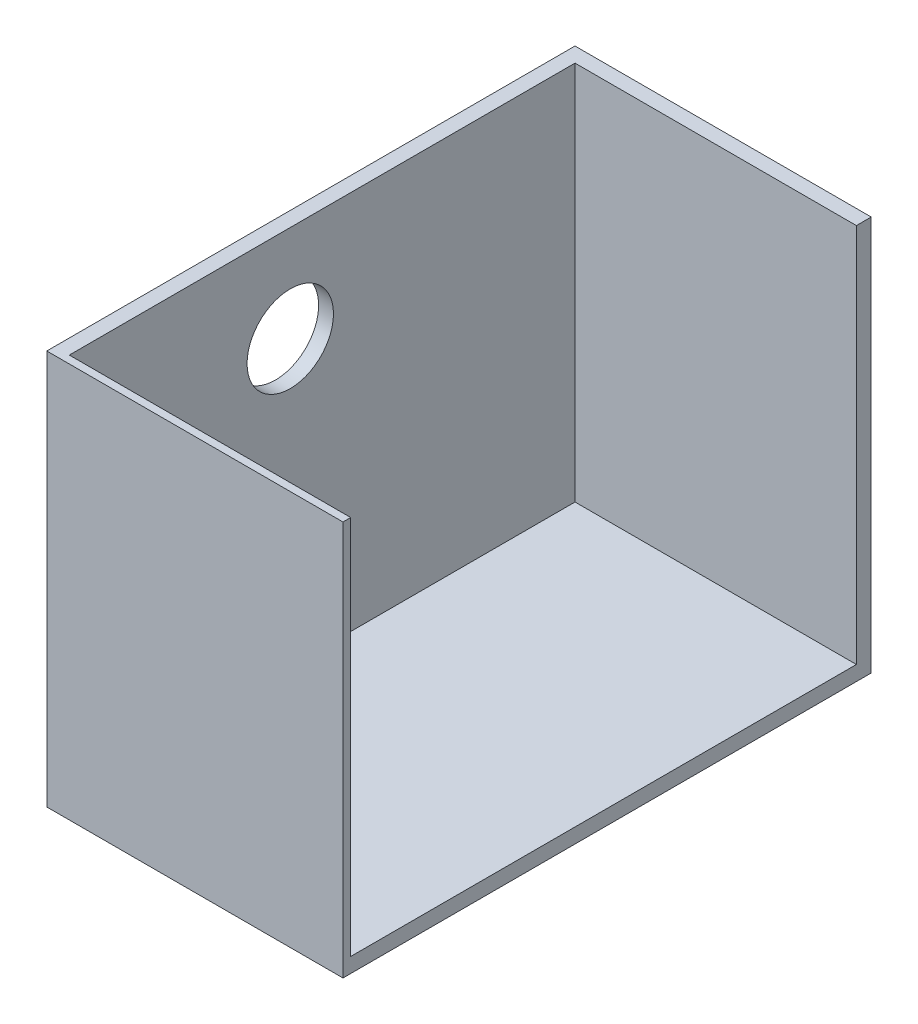
SolidWorks part; units mm, degrees
ref_plane "Front Plane" through (0, 0, 0) normal (0, 0, 1) x (1, 0, 0)
ref_plane "Top Plane" through (0, 0, 0) normal (0, 1, 0) x (1, 0, 0)
ref_plane "Right Plane" through (0, 0, 0) normal (1, 0, 0) x (0, 0, -1)
sketch "Sketch1" plane through (0, 0, 0) normal (0, 1, 0) x (1, 0, 0)
  line L1 (-60, -107) -> (60, -107)
  line L2 (-60, -107) -> (-60, 107)
  line L3 (-60, 107) -> (60, 107)
  line L4 (60, -107) -> (60, 107)
  line L5 (-60, -107) -> (60, 107) construction
  line L6 (-60, 107) -> (60, -107) construction
  point P0 (0, 0)
  dimension "D1" = 120
  dimension "D2" = 214
extrude "Boss-Extrude1" add sketch "Sketch1" along normal blind 160
fillet "Fillet1" [suppressed] radius 80
fillet "Fillet4" [suppressed] radius 30
fillet "Fillet3" [suppressed] radius 80
shell "Shell1" thickness 6
ref_plane "Plane1" through (0, 101, 0) normal (0, -1, 0) x (-1, 0, 0)
sketch "Sketch4" plane through (-60, 0, 0) normal (-1, 0, 0) x (0, 0, 1)
  circle A0 centre (14.3615, 120.977) radius 17.5
  dimension "D1" = 35
extrude "Cut-Extrude1" cut sketch "Sketch4" against normal up to next
